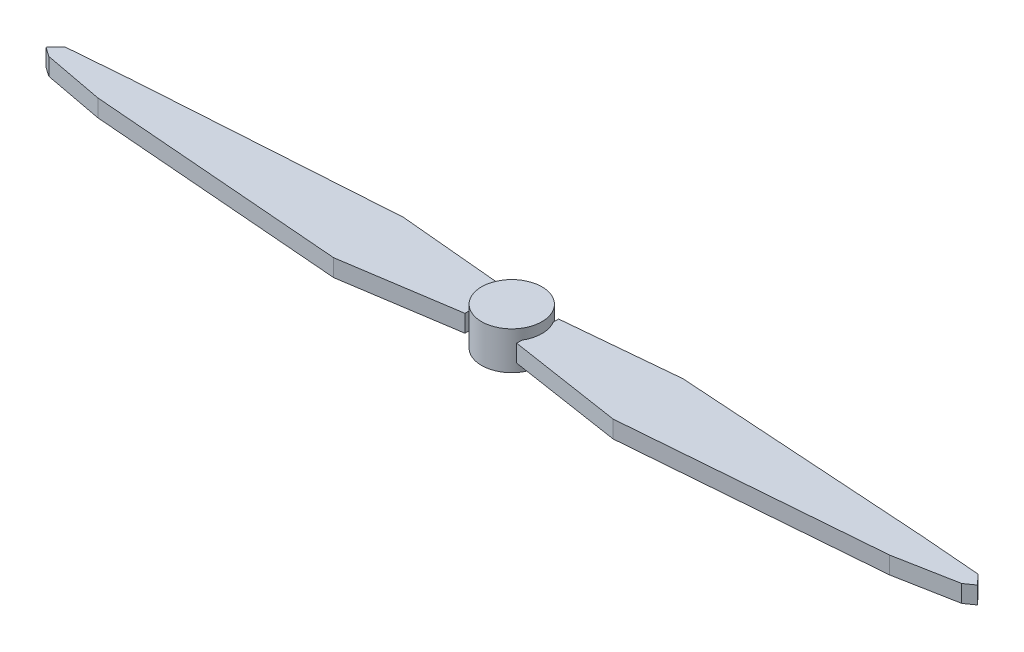
SolidWorks part; units mm, degrees
ref_plane "Front Plane" through (0, 0, 0) normal (0, 0, 1) x (1, 0, 0)
ref_plane "Top Plane" through (0, 0, 0) normal (0, 1, 0) x (1, 0, 0)
ref_plane "Right Plane" through (0, 0, 0) normal (1, 0, 0) x (0, 0, -1)
sketch "Sketch1" plane through (0, 0, 0) normal (0, 1, 0) x (1, 0, 0)
  line L0 (12, -9.7155) -> (64.77, -17.8117)
  line L1 (64.77, -17.8117) -> (183.515, -8.3122)
  line L2 (183.515, -8.3122) -> (211.582, -3.0226)
  line L3 (211.582, -3.0226) -> (215.9, 0)
  line L4 (215.9, 0) -> (211.582, 4.5339)
  line L5 (211.582, 4.5339) -> (183.515, 6.8009)
  line L6 (183.515, 6.8009) -> (64.77, 14.5732)
  line L7 (64.77, 14.5732) -> (12, 9.7155)
  line L8 (12, 9.7155) -> (12, -9.7155)
  line L9 (-12, -9.7155) -> (-64.77, -17.8117)
  line L10 (-64.77, -17.8117) -> (-183.515, -8.3122)
  line L11 (-183.515, -8.3122) -> (-211.582, -3.0226)
  line L12 (-211.582, -3.0226) -> (-215.9, 0)
  line L13 (-215.9, 0) -> (-211.582, 4.5339)
  line L14 (-211.582, 4.5339) -> (-183.515, 6.8009)
  line L15 (-183.515, 6.8009) -> (-64.77, 14.5732)
  line L16 (-64.77, 14.5732) -> (-12, 9.7155)
  line L17 (-12, 9.7155) -> (-12, -9.7155)
extrude "Boss-Extrude1" add sketch "Sketch1" along normal mid plane 8
sketch "Sketch2" plane through (0, 0, 0) normal (0, 1, 0) x (1, 0, 0)
  circle A0 centre (0, 0) radius 14
extrude "Boss-Extrude2" add sketch "Sketch2" along normal mid plane 17.6
